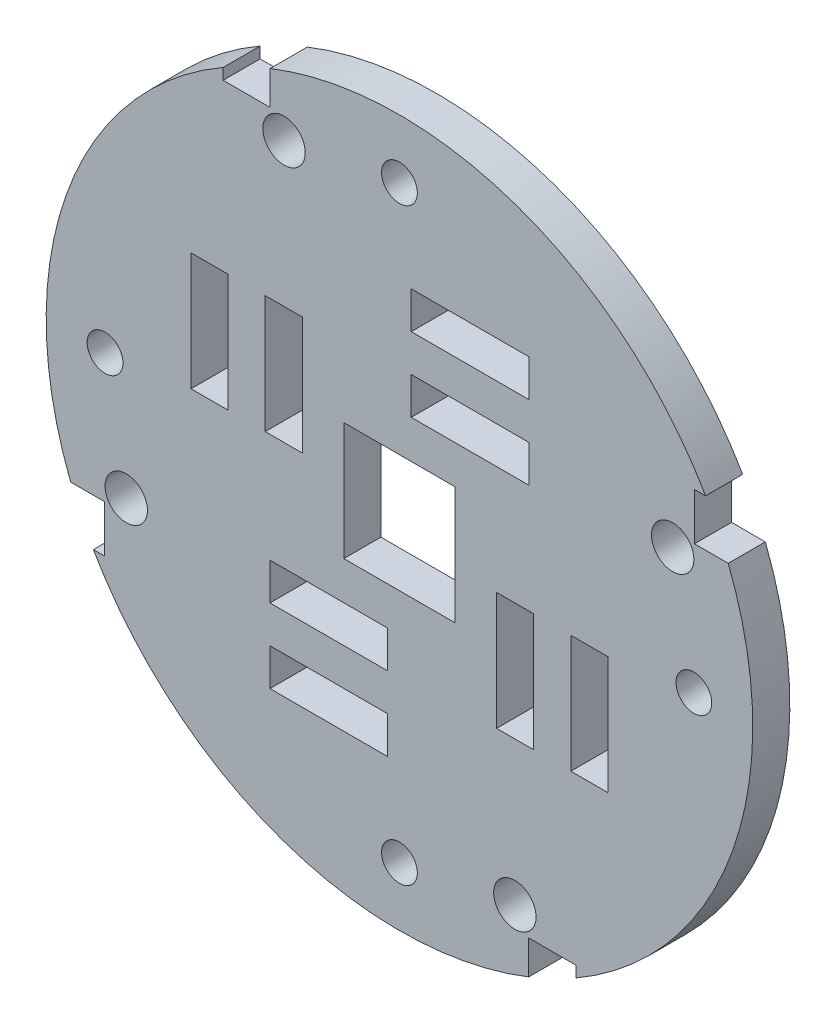
SolidWorks part; units mm, degrees
material "Hexcel AS4C (3000 Filaments)"
ref_plane "Front Plane" through (0, 0, 0) normal (0, 0, 1) x (1, 0, 0)
ref_plane "Top Plane" through (0, 0, 0) normal (0, 1, 0) x (1, 0, 0)
ref_plane "Right Plane" through (0, 0, 0) normal (1, 0, 0) x (0, 0, -1)
sketch "Sketch1" plane through (0, 0, 0) normal (0, 0, 1) x (1, 0, 0)
  circle A0 centre (0, 0) radius 38.1
  dimension "D1" = 76.2
extrude "Boss-Extrude1" add sketch "Sketch1" along normal blind 4 contours A0
sketch "Sketch2" plane through (0, 0, 4) normal (0, 0, 1) x (1, 0, 0)
  line L0 (-1.27, -10.478) -> (-13.97, -10.478)
  line L1 (10.478, -1.27) -> (14.478, -1.27)
  line L2 (10.478, -1.27) -> (10.478, -13.97)
  line L3 (10.478, -13.97) -> (14.478, -13.97)
  line L4 (14.478, -1.27) -> (14.478, -13.97)
  line L5 (18.478, -1.27) -> (22.478, -1.27)
  line L6 (18.478, -1.27) -> (18.478, -13.97)
  line L7 (18.478, -13.97) -> (22.478, -13.97)
  line L8 (22.478, -1.27) -> (22.478, -13.97)
  line L9 (-1.27, -10.478) -> (-1.27, -14.478)
  line L10 (-1.27, -14.478) -> (-13.97, -14.478)
  line L11 (-13.97, -10.478) -> (-13.97, -14.478)
  line L12 (-1.27, -18.478) -> (-13.97, -18.478)
  line L13 (-1.27, -18.478) -> (-1.27, -22.478)
  line L14 (-1.27, -22.478) -> (-13.97, -22.478)
  line L15 (-13.97, -18.478) -> (-13.97, -22.478)
  line L16 (-10.478, 1.27) -> (-10.478, 13.97)
  line L17 (-10.478, 1.27) -> (-14.478, 1.27)
  line L18 (-14.478, 1.27) -> (-14.478, 13.97)
  line L19 (-10.478, 13.97) -> (-14.478, 13.97)
  line L20 (-18.478, 1.27) -> (-18.478, 13.97)
  line L21 (-18.478, 1.27) -> (-22.478, 1.27)
  line L22 (-22.478, 1.27) -> (-22.478, 13.97)
  line L23 (-18.478, 13.97) -> (-22.478, 13.97)
  line L24 (1.27, 10.478) -> (13.97, 10.478)
  line L25 (1.27, 10.478) -> (1.27, 14.478)
  line L26 (1.27, 14.478) -> (13.97, 14.478)
  line L27 (13.97, 10.478) -> (13.97, 14.478)
  line L28 (1.27, 18.478) -> (13.97, 18.478)
  line L29 (1.27, 18.478) -> (1.27, 22.478)
  line L30 (1.27, 22.478) -> (13.97, 22.478)
  line L31 (13.97, 18.478) -> (13.97, 22.478)
  circle A0 centre (12.446, -29.464) radius 2.286
  circle A1 centre (-29.464, -12.446) radius 2.286
  circle A2 centre (-12.446, 29.464) radius 2.286
  circle A3 centre (29.464, 12.446) radius 2.286
  point P12 (14.478, -7.62)
  point P37 (0, 0)
  point P45 (0, 0)
  dimension "D8" = 4.572
  dimension "D1" = 4
  dimension "D2" = 4
  dimension "D3" = 4
  dimension "D4" = 12.7
  dimension "D5" = 14.478
  dimension "D6" = 1.27
  dimension "D9" = 21.844
  dimension "D11" = 2.032
  dimension "D7" = 4
  dimension "D10" = 4
extrude "Cut-Extrude1" cut sketch "Sketch2" against normal through all
sketch "Sketch3" plane through (0, 0, 4) normal (0, 0, 1) x (1, 0, 0)
  line L1 (-6, -6.35) -> (6, -6.35)
  line L2 (-6, -6.35) -> (-6, 6.35)
  line L3 (-6, 6.35) -> (6, 6.35)
  line L4 (6, -6.35) -> (6, 6.35)
  line L5 (-6, -6.35) -> (6, 6.35) construction
  line L6 (-6, 6.35) -> (6, -6.35) construction
  point P0 (0, 0)
  dimension "D1" = 12
  dimension "D2" = 12.7
extrude "Cut-Extrude2" cut sketch "Sketch3" against normal up to next
sketch "Sketch4" plane through (0, 0, 4) normal (0, 0, 1) x (1, 0, 0)
  circle A0 centre (0, -31.75) radius 1.9304
  circle A1 centre (31.75, 0) radius 1.9304
  circle A2 centre (0, 31.75) radius 1.9304
  circle A3 centre (-31.75, 0) radius 1.9304
  point P9 (0, 0)
  dimension "D1" = 3.8608
  dimension "D2" = 31.75
  dimension "D3" = 4
extrude "Cut-Extrude3" cut sketch "Sketch4" against normal through all
sketch "Sketch5" plane through (0, 0, 4) normal (0, 0, 1) x (1, 0, 0)
  line L0 (13.97, 18.478) -> (13.97, 14.478) construction
  line L1 (31.8124, 13.938) -> (36.8924, 13.938)
  line L2 (31.8124, 13.938) -> (31.8124, 19.018)
  line L3 (31.8124, 19.018) -> (36.8924, 19.018)
  line L4 (36.8924, 13.938) -> (36.8924, 19.018)
  line L5 (31.8124, 13.938) -> (36.8924, 19.018) construction
  line L6 (31.8124, 19.018) -> (36.8924, 13.938) construction
  line L7 (13.938, -31.8124) -> (19.018, -31.8124)
  line L8 (13.938, -31.8124) -> (13.938, -36.8924)
  line L9 (13.938, -36.8924) -> (19.018, -36.8924)
  line L10 (19.018, -31.8124) -> (19.018, -36.8924)
  line L11 (-31.8124, -13.938) -> (-31.8124, -19.018)
  line L12 (-31.8124, -13.938) -> (-36.8924, -13.938)
  line L13 (-36.8924, -13.938) -> (-36.8924, -19.018)
  line L14 (-31.8124, -19.018) -> (-36.8924, -19.018)
  line L15 (-13.938, 31.8124) -> (-19.018, 31.8124)
  line L16 (-13.938, 31.8124) -> (-13.938, 36.8924)
  line L17 (-13.938, 36.8924) -> (-19.018, 36.8924)
  line L18 (-19.018, 31.8124) -> (-19.018, 36.8924)
  circle A0 centre (0, 0) radius 38.1 construction
  point P0 (34.3524, 16.478)
  point P11 (0, -0.8859)
  point P12 (13.97, 16.478)
  point P13 (0, 0)
  point P27 (0, 0)
  dimension "D1" = 5.08
  dimension "D2" = 5.08
  dimension "D3" = 4
extrude "Cut-Extrude4" cut sketch "Sketch5" against normal up to next
